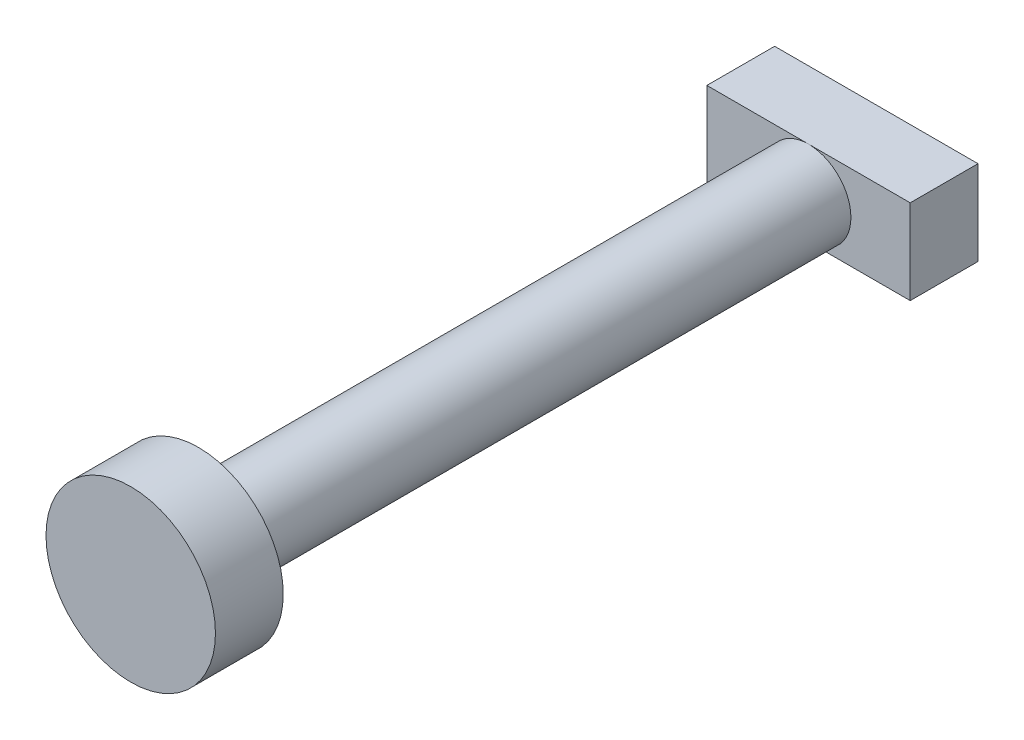
SolidWorks part; units mm, degrees
ref_plane "Front Plane" through (0, 0, 0) normal (0, 0, 1) x (1, 0, 0)
ref_plane "Top Plane" through (0, 0, 0) normal (0, 1, 0) x (1, 0, 0)
ref_plane "Right Plane" through (0, 0, 0) normal (1, 0, 0) x (0, 0, -1)
sketch "Sketch1" plane through (0, 0, 0) normal (0, 0, 1) x (1, 0, 0)
  circle A0 centre (0, 0) radius 1.25
  dimension "D1" = 2.5
extrude "Boss-Extrude1" add sketch "Sketch1" along normal mid plane 18
sketch "Sketch2" plane through (0, 0, 9) normal (0, 0, 1) x (1, 0, 0)
  circle A0 centre (0, 0) radius 2.5
  dimension "D1" = 5
extrude "Boss-Extrude2" add sketch "Sketch2" along normal blind 2
sketch "Sketch3" plane through (0, 0, -9) normal (0, 0, -1) x (-1, 0, 0)
  line L1 (-3, -1.25) -> (3, -1.25)
  line L2 (-3, -1.25) -> (-3, 1.25)
  line L3 (-3, 1.25) -> (3, 1.25)
  line L4 (3, -1.25) -> (3, 1.25)
  line L5 (-3, -1.25) -> (3, 1.25) construction
  line L6 (-3, 1.25) -> (3, -1.25) construction
  point P0 (0, 0)
  dimension "D1" = 6
  dimension "D2" = 2.5
extrude "Boss-Extrude3" add sketch "Sketch3" along normal blind 2
